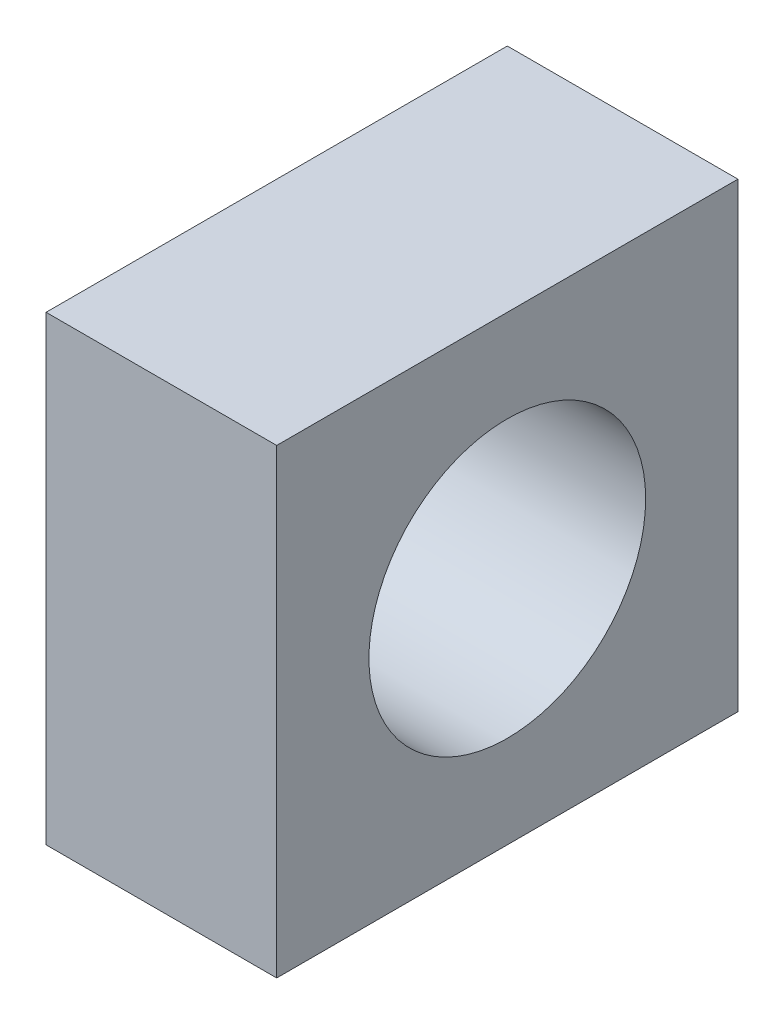
SolidWorks part; units mm, degrees
ref_plane "前视基准面" through (0, 0, 0) normal (0, 0, 1) x (1, 0, 0)
ref_plane "上视基准面" through (0, 0, 0) normal (0, 1, 0) x (1, 0, 0)
ref_plane "右视基准面" through (0, 0, 0) normal (1, 0, 0) x (0, 0, -1)
other "Configuration Table"
sketch "草图1" plane through (0, 0, 0) normal (1, 0, 0) x (0, 0, -1)
  line L1 (-1, -1) -> (1, -1)
  line L2 (-1, -1) -> (-1, 1)
  line L3 (-1, 1) -> (1, 1)
  line L4 (1, -1) -> (1, 1)
  line L5 (-1, -1) -> (1, 1) construction
  line L6 (-1, 1) -> (1, -1) construction
  circle A0 centre (0, 0) radius 0.6
  point P0 (0, 0)
  dimension "D1" = 1.2
  dimension "D2" = 1
  dimension "D3" = 2
extrude "凸台-拉伸2" add sketch "草图1" along normal blind 1 contours L1 L4 L3 L2 | A0
